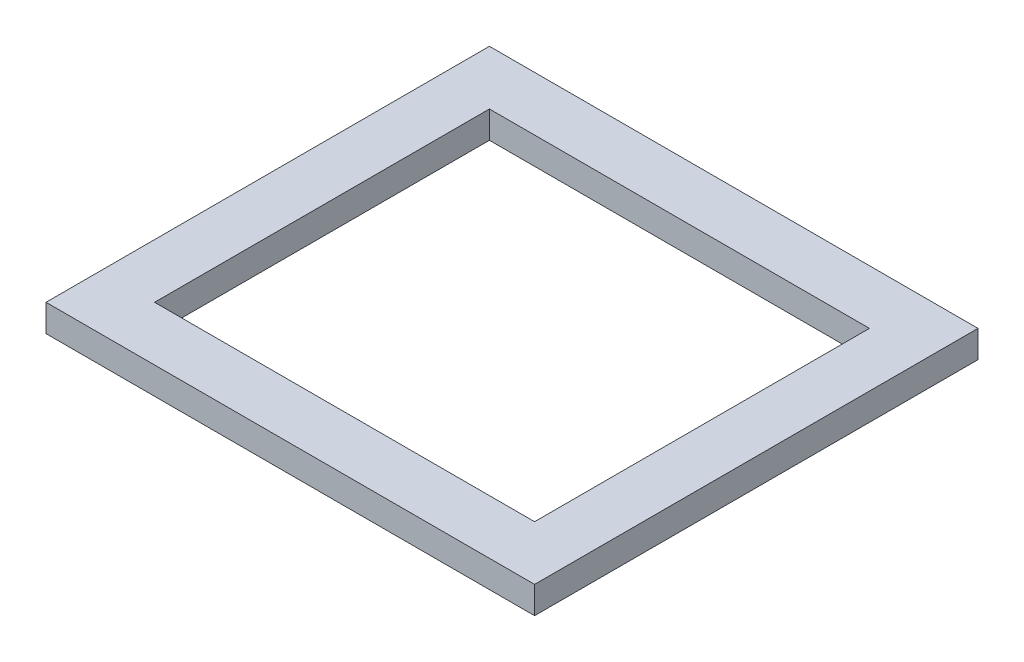
SolidWorks part; units mm, degrees
ref_plane "Front Plane" through (0, 0, 0) normal (0, 0, 1) x (1, 0, 0)
ref_plane "Top Plane" through (0, 0, 0) normal (0, 1, 0) x (1, 0, 0)
ref_plane "Right Plane" through (0, 0, 0) normal (1, 0, 0) x (0, 0, -1)
sketch "Sketch1" plane through (0, 0, 0) normal (0, 1, 0) x (1, 0, 0)
  line L1 (0, 0) -> (44.45, 0)
  line L2 (0, 0) -> (0, 39.1668)
  line L3 (0, 39.1668) -> (44.45, 39.1668)
  line L4 (44.45, 0) -> (44.45, 39.1668)
  line L5 (-6.35, 45.5168) -> (50.8, 45.5168)
  line L6 (-6.35, 45.5168) -> (-6.35, -6.35)
  line L7 (-6.35, -6.35) -> (50.8, -6.35)
  line L8 (50.8, 45.5168) -> (50.8, -6.35)
  dimension "D1" = 39.1668
  dimension "D2" = 44.45
  dimension "D3" = 51.8668
  dimension "D4" = 57.15
  dimension "D5" = 6.35
  dimension "D6" = 6.35
extrude "Boss-Extrude1" add sketch "Sketch1" along normal blind 3.175
